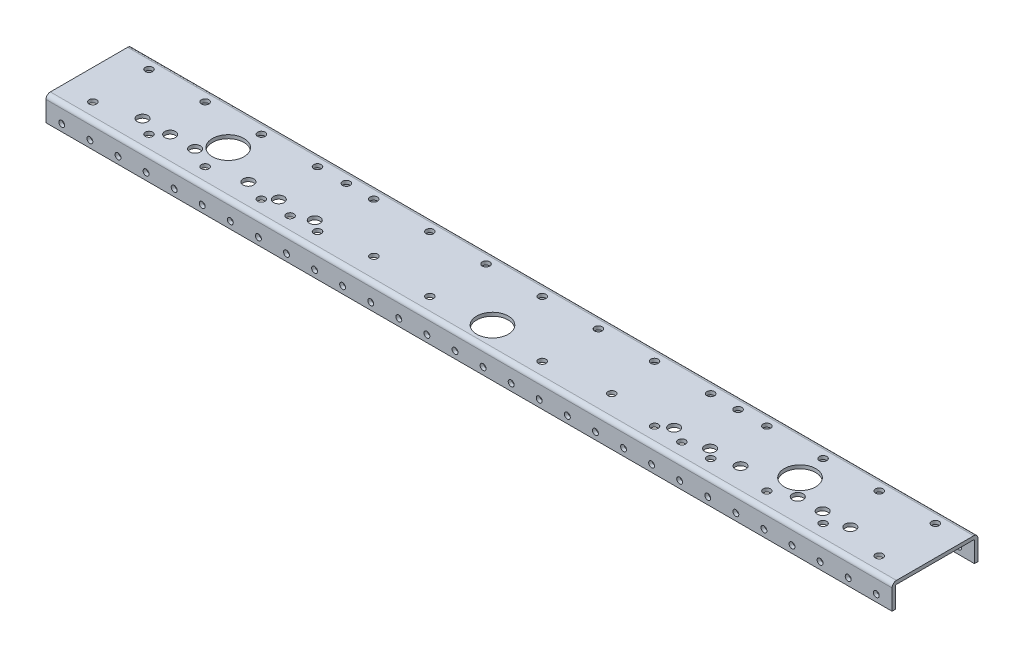
SolidWorks part; units mm, degrees
ref_plane "Front Plane" through (0, 0, 0) normal (0, 0, 1) x (1, 0, 0)
ref_plane "Top Plane" through (0, 0, 0) normal (0, 1, 0) x (1, 0, 0)
ref_plane "Right Plane" through (0, 0, 0) normal (1, 0, 0) x (0, 0, -1)
ref_plane "Plane1" through (0, -19.05, 0) normal (0, -1, 0) x (1, 0, 0)
sketch "Sketch1" plane through (0, -19.05, 0) normal (0, -1, 0) x (1, 0, 0)
  line L0 (812.8, 3.937) -> (0, 3.937)
  line L1 (0, 3.937) -> (0, -73.787)
  line L2 (0, -73.787) -> (812.8, -73.787)
  line L3 (812.8, -73.787) -> (812.8, 3.937)
extrude "Boss-Extrude1" add sketch "Sketch1" against normal blind 22.225
sketch "Sketch2" plane through (0, 0, 0) normal (-1, 0, 0) x (0, 0, 1)
  line L0 (-70.612, -19.05) -> (0.762, -19.05)
  line L1 (0.762, -19.05) -> (0.762, 0)
  line L2 (0.762, 0) -> (-70.612, 0)
  line L3 (-70.612, 0) -> (-70.612, -19.05)
extrude "Cut-Extrude1" cut sketch "Sketch2" against normal through all
hole_wizard "Hole1" positions "Sketch4" profile "Sketch3" legacy
sketch "Sketch4" plane through (0, 0, 0) normal (0, -1, 0) x (-1, 0, 0)
  point P0 (-568.9249, 19.05)
  point P1 (-601.4385, 19.05)
  point P2 (-628.9477, 19.05)
  point P3 (-243.8751, 19.05)
  point P4 (-211.3615, 19.05)
  point P5 (-183.8523, 19.05)
  point P6 (-678.9442, 20.828)
  point P7 (-701.4504, 20.828)
  point P8 (-726.4609, 20.828)
  point P9 (-133.8558, 20.828)
  point P10 (-111.3496, 20.828)
  point P11 (-86.3391, 20.828)
sketch "Sketch3" plane through (568.9249, 0, -19.05) normal (1, 0, 0) x (0, 0, -1)
  line L0 (0, 0) -> (0, 3.175)
  line L1 (0, 3.175) -> (4.826, 3.175)
  line L2 (4.826, 3.175) -> (4.826, 0)
  line L3 (4.826, 0) -> (0, 0)
  line L4 (0, 110) -> (0, -10) construction
  dimension "Diameter" = 9.652
  dimension "Depth" = 3.175
hole_wizard "Hole2" positions "Sketch6" profile "Sketch5" legacy
sketch "Sketch6" plane through (0, 0, 0) normal (0, -1, 0) x (-1, 0, 0)
  point P0 (-664.9708, 36.83)
  point P1 (-147.8292, 36.83)
  point P2 (-406.4, 17.272)
sketch "Sketch5" plane through (664.9708, 0, -36.83) normal (1, 0, 0) x (0, 0, -1)
  line L0 (0, 0) -> (0, 3.175)
  line L1 (0, 3.175) -> (14.2875, 3.175)
  line L2 (14.2875, 3.175) -> (14.2875, 0)
  line L3 (14.2875, 0) -> (0, 0)
  line L4 (0, 110) -> (0, -10) construction
  dimension "Diameter" = 28.575
  dimension "Depth" = 3.175
hole_wizard "H (0.266) Diameter Hole1" positions "Sketch8" profile "Sketch7" hole size "H" standard "ANSI Inch"
sketch "Sketch8" plane through (0, 0, 0) normal (0, -1, 0) x (-1, 0, 0)
  point P0 (-762, 11.43)
  point P1 (-762, 62.23)
  point P2 (-711.2, 11.43)
  point P3 (-711.2, 62.23)
  point P4 (-660.4, 11.43)
  point P5 (-660.4, 62.23)
  point P6 (-609.6, 11.43)
  point P7 (-609.6, 62.23)
  point P8 (-558.8, 11.43)
  point P9 (-558.8, 62.23)
  point P10 (-152.4, 11.43)
  point P11 (-203.2, 62.23)
  point P12 (-203.2, 11.43)
  point P13 (-254, 62.23)
  point P14 (-50.8, 11.43)
  point P15 (-101.6, 62.23)
  point P16 (-101.6, 11.43)
  point P17 (-152.4, 62.23)
  point P18 (-254, 11.43)
  point P19 (-304.8, 62.23)
  point P20 (-355.6, 62.23)
  point P21 (-355.6, 11.43)
  point P22 (-508, 62.23)
  point P23 (-457.2, 11.43)
  point P24 (-457.2, 62.23)
  point P25 (-406.4, 62.23)
  point P26 (-50.8, 62.23)
  point P27 (-583.5384, 62.23)
  point P28 (-583.5384, 11.43)
  point P29 (-229.2616, 11.43)
  point P30 (-229.2616, 62.23)
  point P31 (-513.9255, 17.5473)
  point P32 (-298.8745, 17.5473)
sketch "Sketch7" plane through (762, 0, -11.43) normal (1, 0, 0) x (0, 0, -1)
  line L0 (0, 0) -> (0, 3.175)
  line L1 (0, 3.175) -> (3.3782, 3.175)
  line L2 (3.3782, 3.175) -> (3.3782, 0)
  line L5 (3.3782, 0) -> (0, 0)
  line L11 (0, -6.35) -> (0, 107.95) construction
  dimension "Thru Hole Dia." = 6.7564
  dimension "Thru Hole Depth" = 3.175
hole_wizard "#10 Clearance Hole1" positions "Sketch10" profile "Sketch9" hole size "#10" standard "ANSI Inch"
sketch "Sketch10" plane through (0, 0, 0.762) normal (0, 0, -1) x (-1, 0, 0)
  point P0 (-12.7, -12.7)
  point P1 (-800.1, -12.7)
sketch "Sketch9" plane through (12.7, -12.7, 0.762) normal (1, 0, 0) x (0, 1, 0)
  line L0 (0, 0) -> (0, 3.175)
  line L1 (0, 3.175) -> (2.667, 3.175)
  line L2 (2.667, 3.175) -> (2.667, 0)
  line L5 (2.667, 0) -> (0, 0)
  line L11 (0, -6.35) -> (0, 107.95) construction
  dimension "Thru Hole Dia." = 5.334
  dimension "Thru Hole Depth" = 3.175
hole_wizard "#10 Clearance Hole2" positions "Sketch12" profile "Sketch11" hole size "#10" standard "ANSI Inch"
sketch "Sketch12" plane through (0, 0, 3.937) normal (0, 0, 1) x (1, 0, 0)
  point P0 (63.5, -12.7)
  point P1 (38.1, -12.7)
  point P2 (88.9, -12.7)
  point P3 (114.3, -12.7)
  point P4 (139.7, -12.7)
  point P5 (165.1, -12.7)
  point P6 (190.5, -12.7)
  point P7 (215.9, -12.7)
  point P8 (241.3, -12.7)
  point P9 (266.7, -12.7)
  point P10 (292.1, -12.7)
  point P11 (317.5, -12.7)
  point P12 (342.9, -12.7)
  point P13 (368.3, -12.7)
  point P14 (393.7, -12.7)
  point P15 (419.1, -12.7)
  point P16 (444.5, -12.7)
  point P17 (469.9, -12.7)
  point P18 (495.3, -12.7)
  point P19 (520.7, -12.7)
  point P20 (546.1, -12.7)
  point P21 (571.5, -12.7)
  point P22 (596.9, -12.7)
  point P23 (622.3, -12.7)
  point P24 (647.7, -12.7)
  point P25 (673.1, -12.7)
  point P26 (698.5, -12.7)
  point P27 (723.9, -12.7)
  point P28 (749.3, -12.7)
  point P29 (774.7, -12.7)
sketch "Sketch11" plane through (63.5, -12.7, 3.937) normal (1, 0, 0) x (0, -1, 0)
  line L0 (0, 0) -> (0, 3.175)
  line L1 (0, 3.175) -> (2.667, 3.175)
  line L2 (2.667, 3.175) -> (2.667, 0)
  line L5 (2.667, 0) -> (0, 0)
  line L11 (0, -6.35) -> (0, 107.95) construction
  dimension "Thru Hole Dia." = 5.334
  dimension "Thru Hole Depth" = 3.175
hole_wizard "#10 Clearance Hole3" positions "Sketch14" profile "Sketch13" hole size "#10" standard "ANSI Inch"
sketch "Sketch14" plane through (0, 0, -70.612) normal (0, 0, 1) x (1, 0, 0)
  point P0 (800.1, -12.7)
  point P1 (774.7, -12.7)
  point P2 (749.3, -12.7)
  point P3 (723.9, -12.7)
  point P4 (698.5, -12.7)
  point P5 (673.1, -12.7)
  point P6 (647.7, -12.7)
  point P7 (622.3, -12.7)
  point P8 (596.9, -12.7)
  point P9 (571.5, -12.7)
  point P10 (546.1, -12.7)
  point P11 (520.7, -12.7)
  point P12 (495.3, -12.7)
  point P13 (469.9, -12.7)
  point P14 (444.5, -12.7)
  point P15 (419.1, -12.7)
  point P16 (393.7, -12.7)
  point P17 (368.3, -12.7)
  point P18 (342.9, -12.7)
  point P19 (317.5, -12.7)
  point P20 (292.1, -12.7)
  point P21 (266.7, -12.7)
  point P22 (241.3, -12.7)
  point P23 (215.9, -12.7)
  point P24 (190.5, -12.7)
  point P25 (165.1, -12.7)
  point P26 (139.7, -12.7)
  point P27 (114.3, -12.7)
  point P28 (88.9, -12.7)
  point P29 (63.5, -12.7)
  point P30 (38.1, -12.7)
  point P31 (12.7, -12.7)
sketch "Sketch13" plane through (800.1, -12.7, -70.612) normal (1, 0, 0) x (0, -1, 0)
  line L0 (0, 0) -> (0, 3.175)
  line L1 (0, 3.175) -> (2.667, 3.175)
  line L2 (2.667, 3.175) -> (2.667, 0)
  line L5 (2.667, 0) -> (0, 0)
  line L11 (0, -6.35) -> (0, 107.95) construction
  dimension "Thru Hole Dia." = 5.334
  dimension "Thru Hole Depth" = 3.175
chamfer "Chamfer1" distance 3.175 angle 45 4 edges at (812.8, -19.05, -72.1995) (812.8, -19.05, 2.3495) (0, -19.05, -72.1995) (0, -19.05, 2.3495)
fillet "Fillet1" radius 0.762 2 edges at (406.4, 0, 0.762) (406.4, 0, -70.612)
fillet "Fillet2" radius 3.937 2 edges at (406.4, 3.175, 3.937) (406.4, 3.175, -73.787)
sketch "Sketch15" plane through (0, 3.175, 0) normal (0, 1, 0) x (1, 0, 0)
  line L0 (0, 73.787) -> (812.8, 73.787) construction
  line L1 (23.8125, 73.787) -> (788.9875, 73.787)
  line L2 (23.8125, 73.787) -> (23.8125, -3.937)
  line L3 (23.8125, -3.937) -> (788.9875, -3.937)
  line L4 (788.9875, 73.787) -> (788.9875, -3.937)
  line L5 (812.8, -3.937) -> (0, -3.937) construction
  line L6 (0, -3.937) -> (23.8125, -3.937) construction
  line L7 (812.8, -3.937) -> (788.9875, -3.937) construction
  line L9 (23.8125, -3.937) -> (0, -3.937)
  line L10 (23.8125, -3.937) -> (23.8125, 73.787)
  line L11 (23.8125, 73.787) -> (0, 73.787)
  line L12 (0, -3.937) -> (0, 73.787)
  line L13 (812.8, -3.937) -> (788.9875, -3.937)
  line L14 (812.8, -3.937) -> (812.8, 73.787)
  line L15 (812.8, 73.787) -> (788.9875, 73.787)
  line L16 (788.9875, -3.937) -> (788.9875, 73.787)
  dimension "D1" = 765.175
extrude "Cut-Extrude2" cut sketch "Sketch15" against normal through all contours L14 L15 L4 L13 | L12 L9 L2 L11
